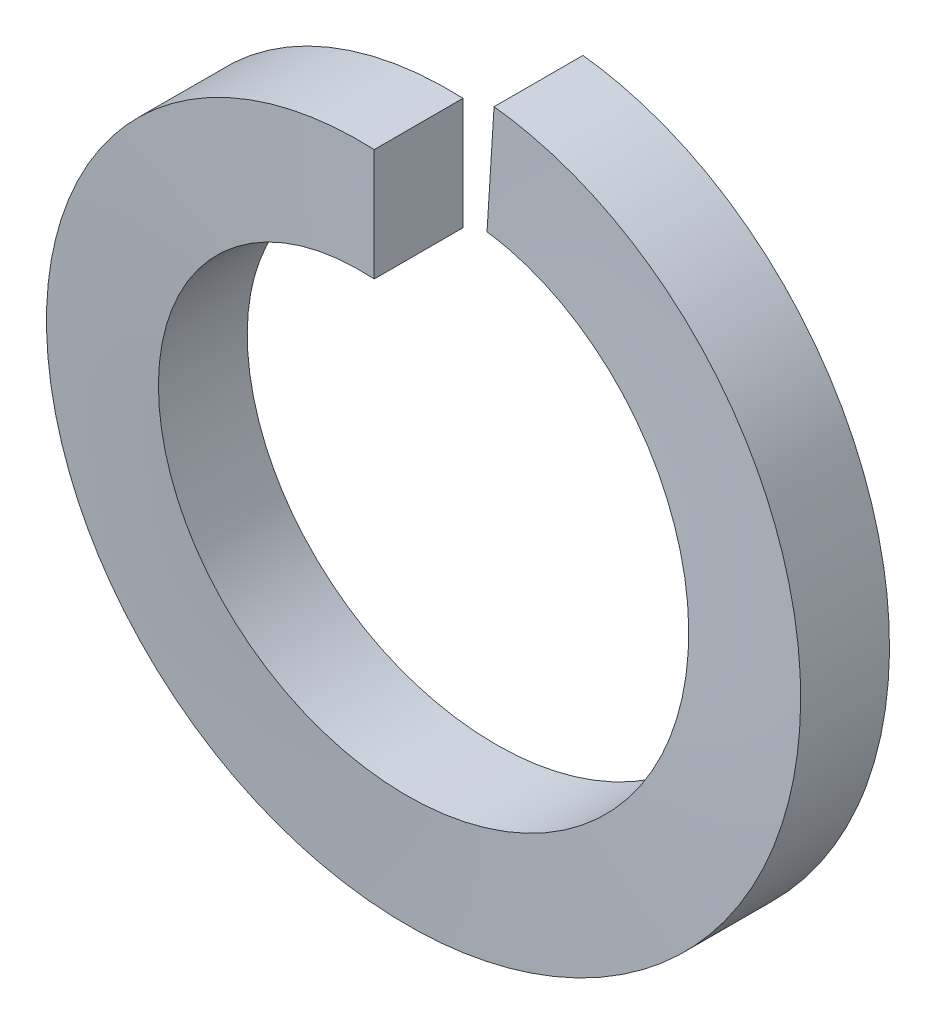
SolidWorks part; units mm, degrees
ref_plane "Front Plane" through (0, 0, 0) normal (0, 0, 1) x (1, 0, 0)
ref_plane "Top Plane" through (0, 0, 0) normal (0, 1, 0) x (1, 0, 0)
ref_plane "Right Plane" through (0, 0, 0) normal (1, 0, 0) x (0, 0, -1)
sketch "Sketch1" plane through (0, 0, 0) normal (0, 0, 1) x (1, 0, 0)
  line L0 (0, 6.242) -> (0, 4.2545) construction
  circle A0 centre (0, 0) radius 6.242
  circle A1 centre (0, 0) radius 4.2545 construction
  dimension "ID" = 8.509
  dimension "OD" = 12.4841
curve "Helix/Spiral1" pitch 1.7498 height 1.7323 turns 0.99 parameters "HT"=1.7323
sketch "Sketch2" plane through (0, 0, 0) normal (1, 0, 0) x (0, 0, -1)
  line L1 (0, 6.242) -> (-1.5748, 6.242)
  line L2 (0, 6.242) -> (0, 4.2545)
  line L3 (0, 4.2545) -> (-1.5748, 4.2545)
  line L4 (-1.5748, 6.242) -> (-1.5748, 4.2545)
  dimension "THK" = 1.5748
sweep "Sweep1" add profiles "Sketch2" path "Helix/Spiral1"
ref_plane "Plane1" through (0, 0, 0) normal (1, 0, 0) x (0, 0, -1)
equation "\"HT@Helix/Spiral1\" = \"THK@Sketch2\"*1.1"
